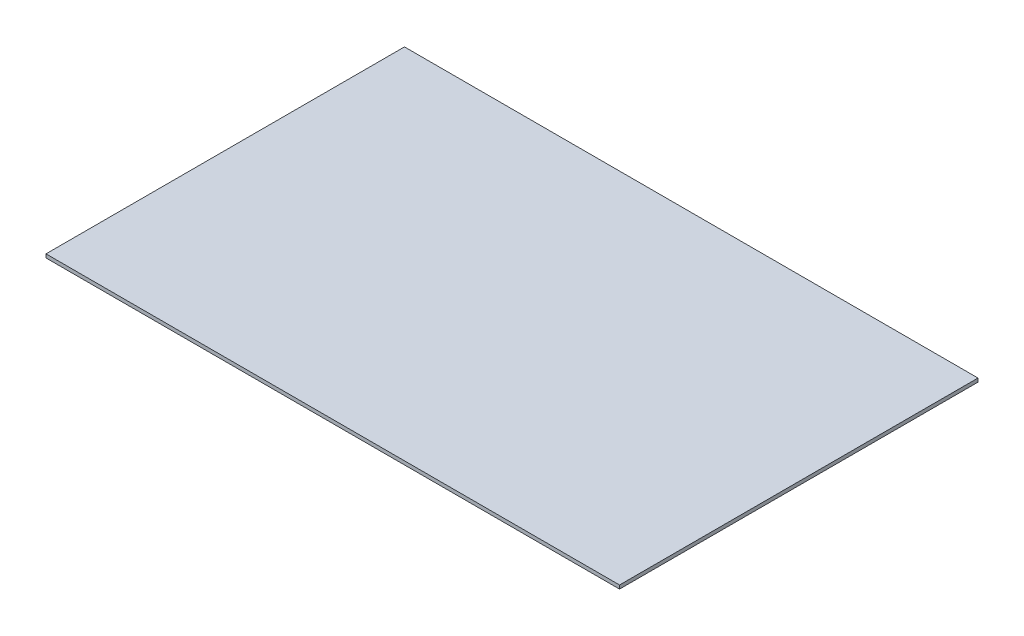
SolidWorks part; units mm, degrees
ref_plane "Plan de face" through (0, 0, 0) normal (0, 0, 1) x (1, 0, 0)
ref_plane "Plan de dessus" through (0, 0, 0) normal (0, 1, 0) x (1, 0, 0)
ref_plane "Plan de droite" through (0, 0, 0) normal (1, 0, 0) x (0, 0, -1)
sketch "Esquisse1" plane through (0, 0, 0) normal (0, 1, 0) x (1, 0, 0)
  line L1 (-400, -250) -> (400, -250)
  line L2 (-400, -250) -> (-400, 250)
  line L3 (-400, 250) -> (400, 250)
  line L4 (400, -250) -> (400, 250)
  line L5 (-400, -250) -> (400, 250) construction
  line L6 (-400, 250) -> (400, -250) construction
  point P0 (0, 0)
  dimension "D1" = 800
  dimension "D2" = 500
extrude "Boss.-Extru.1" add sketch "Esquisse1" along normal blind 5
